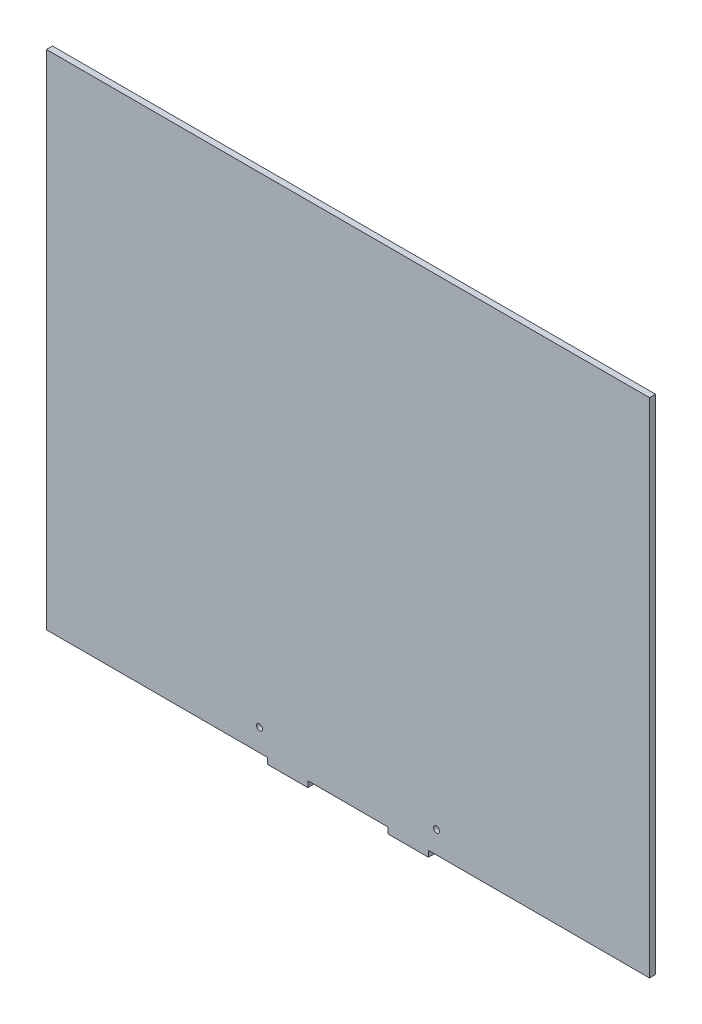
SolidWorks part; units mm, degrees
ref_plane "Plano frontal" through (0, 0, 0) normal (0, 0, 1) x (1, 0, 0)
ref_plane "Plano superior" through (0, 0, 0) normal (0, 1, 0) x (1, 0, 0)
ref_plane "Plano direito" through (0, 0, 0) normal (1, 0, 0) x (0, 0, -1)
sketch "Esboço1" plane through (0, 0, 0) normal (0, 0, 1) x (1, 0, 0)
  line L0 (-182.8366, -107.8709) -> (-72.8366, -107.8709)
  line L1 (-182.8366, 142.1291) -> (117.1634, 142.1291)
  line L2 (-182.8366, 142.1291) -> (-182.8366, -107.8709)
  line L3 (-72.8366, -107.8709) -> (-72.8366, -110.8709)
  line L4 (117.1634, 142.1291) -> (117.1634, -107.8709)
  line L5 (-72.8366, -110.8709) -> (-52.8366, -110.8709)
  line L6 (-52.8366, -110.8709) -> (-52.8366, -107.8709)
  line L7 (-52.8366, -107.8709) -> (-12.8366, -107.8709)
  line L8 (-12.8366, -107.8709) -> (-12.8366, -110.8709)
  line L9 (-12.8366, -110.8709) -> (7.1634, -110.8709)
  line L10 (7.1634, -110.8709) -> (7.1634, -107.8709)
  line L11 (7.1634, -107.8709) -> (117.1634, -107.8709)
  dimension "D1" = 250
  dimension "D2" = 300
  dimension "D3" = 20
  dimension "D4" = 20
  dimension "D5" = 110
  dimension "D6" = 110
  dimension "D7" = 3
  dimension "D8" = 3
  dimension "D9" = 3
extrude "Ressalto-extrusão1" add sketch "Esboço1" along normal blind 3 contours L4 L11 L10 L9 L8 L7 L6 L5 L3 L0 L2 L1
sketch "Esboço3" plane through (0, 0, 0) normal (0, 0, -1) x (-1, 0, 0)
  line L0 (-117.1634, 142.1291) -> (-117.1634, -107.8709) construction
  line L1 (182.8366, 142.1291) -> (182.8366, -107.8709) construction
  line L2 (-7.1634, -107.8709) -> (-117.1634, -107.8709) construction
  line L3 (182.8366, -107.8709) -> (72.8366, -107.8709) construction
  circle A0 centre (-11.1634, -96.8709) radius 1.5
  circle A1 centre (76.8366, -96.8709) radius 1.5
  dimension "D1" = 106
  dimension "D2" = 106
  dimension "D3" = 3
  dimension "D4" = 11
  dimension "D5" = 3
  dimension "D6" = 11
extrude "Corte-extrusão2" cut sketch "Esboço3" against normal through all
